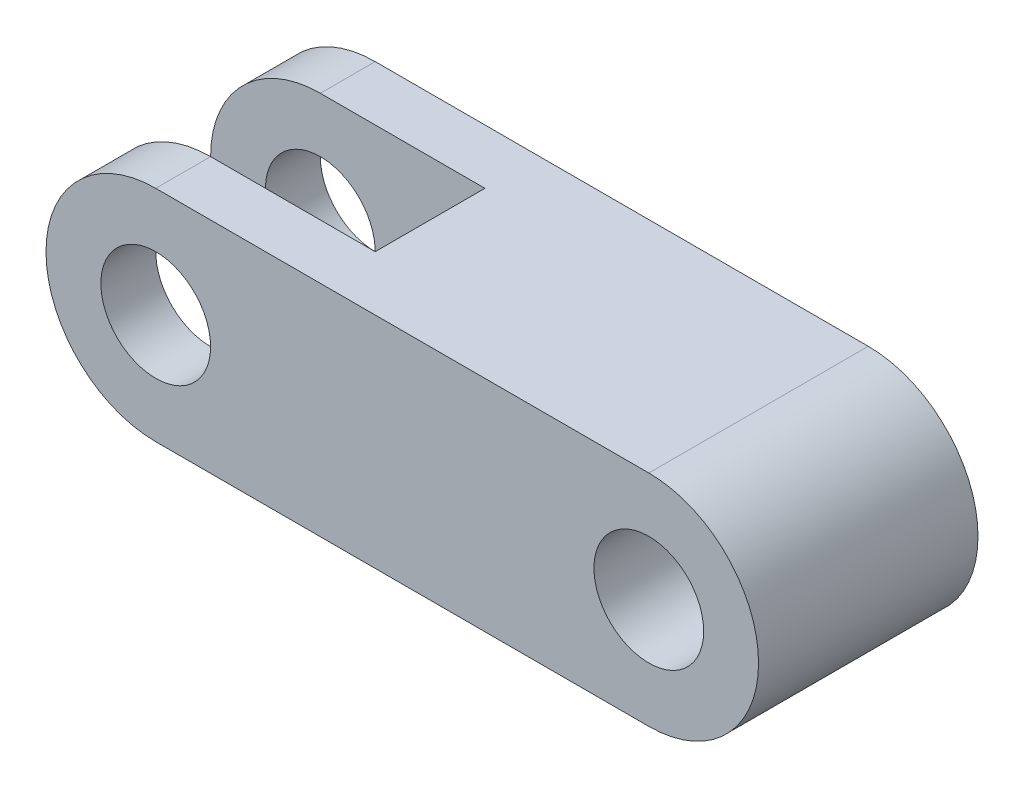
SolidWorks part; units mm, degrees
ref_plane "Front Plane" through (0, 0, 0) normal (0, 0, 1) x (1, 0, 0)
ref_plane "Top Plane" through (0, 0, 0) normal (0, 1, 0) x (1, 0, 0)
ref_plane "Right Plane" through (0, 0, 0) normal (1, 0, 0) x (0, 0, -1)
sketch "Sketch1" plane through (0, 0, 0) normal (0, 0, 1) x (1, 0, 0)
  line L0 (0, 0) -> (44.9358, 0) construction
  line L1 (0, 10) -> (44.9358, 10)
  line L2 (0, -10) -> (44.9358, -10)
  arc A0 (0, 10) -> (0, -10) centre (0, 0) ccw
  arc A1 (44.9358, -10) -> (44.9358, 10) centre (44.9358, 0) ccw
  circle A2 centre (0, 0) radius 5
  circle A3 centre (44.9358, 0) radius 5
  point P3 (22.4679, 0)
  dimension "D1" = 10
  dimension "D2" = 10
  dimension "D3" = 20
extrude "Boss-Extrude1" add sketch "Sketch1" along normal blind 20
sketch "Sketch2" plane through (0, 10, 0) normal (0, 1, 0) x (1, 0, 0)
  line L0 (-10, 0) -> (-10, -20) construction
  line L1 (15, -5) -> (-10, -5)
  line L2 (15, -5) -> (15, -15)
  line L3 (15, -15) -> (-10, -15)
  line L4 (-10, -5) -> (-10, -15)
  line L6 (0, -20) -> (0, 0) construction
  point P7 (-10, -10)
  point P10 (0, -10)
  dimension "D1" = 10
  dimension "D2" = 25
extrude "Cut-Extrude1" cut sketch "Sketch2" against normal through all
